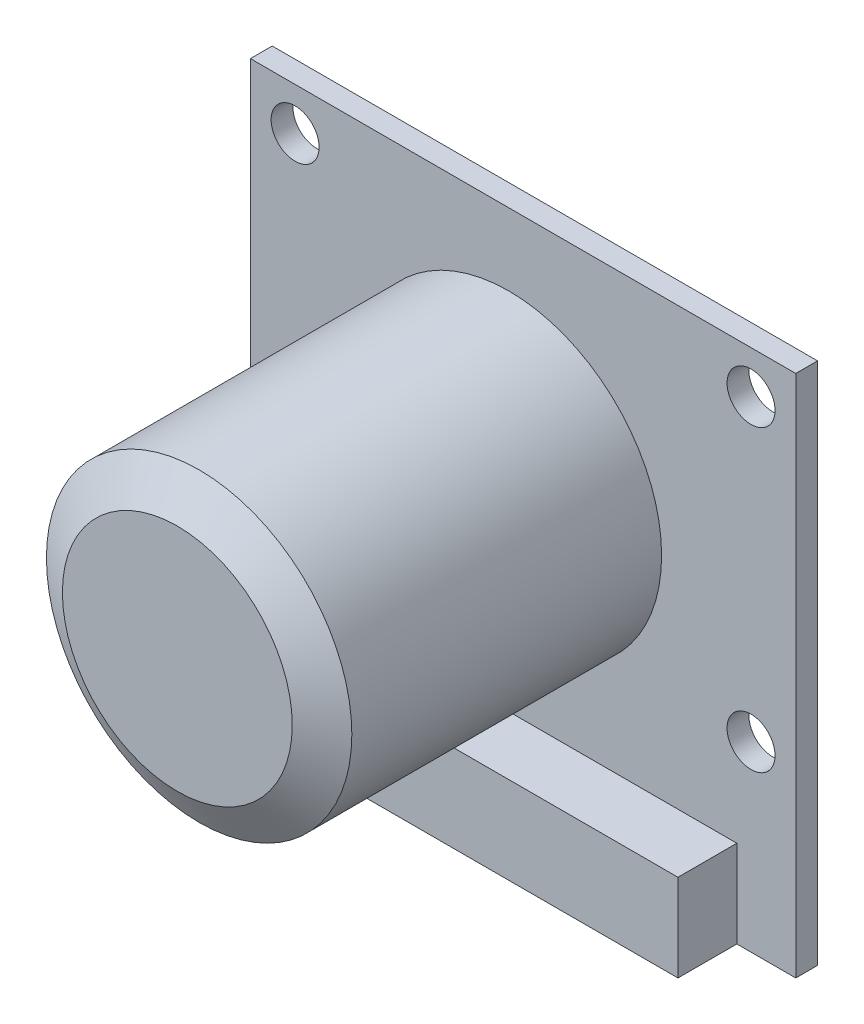
SolidWorks part; units mm, degrees
ref_plane "Plano frontal" through (0, 0, 0) normal (0, 0, 1) x (1, 0, 0)
ref_plane "Plano superior" through (0, 0, 0) normal (0, 1, 0) x (1, 0, 0)
ref_plane "Plano direito" through (0, 0, 0) normal (1, 0, 0) x (0, 0, -1)
sketch "Esboço1" plane through (0, 0, 0) normal (0, 0, 1) x (1, 0, 0)
  line L1 (-12.5, 12) -> (12.5, 12)
  line L2 (-12.5, 12) -> (-12.5, -12)
  line L3 (-12.5, -12) -> (12.5, -12)
  line L4 (12.5, 12) -> (12.5, -12)
  line L5 (-12.5, 12) -> (12.5, -12) construction
  line L6 (-12.5, -12) -> (12.5, 12) construction
  point P0 (0, 0)
  dimension "D1" = 25
  dimension "D2" = 24
extrude "Ressalto-extrusão1" add sketch "Esboço1" along normal blind 1
sketch "Esboço2" plane through (0, 0, 1) normal (0, 0, 1) x (1, 0, 0)
  line L0 (-12.5, -12) -> (12.5, -12) construction
  line L1 (-10.6, -8) -> (9.8, -8)
  line L2 (-10.6, -8) -> (-10.6, -12)
  line L3 (-10.6, -12) -> (9.8, -12)
  line L4 (9.8, -8) -> (9.8, -12)
  line L5 (12.5, -12) -> (12.5, 12) construction
  line L7 (-12.5, 12) -> (-12.5, -12) construction
  dimension "D1" = 4
  dimension "D2" = 20.4
  dimension "D3" = 2.7
  dimension "D4" = 1.9
extrude "Ressalto-extrusão2" add sketch "Esboço2" along normal blind 2.7
sketch "Esboço3" plane through (0, 0, 1) normal (0, 0, 1) x (1, 0, 0)
  line L0 (12.5, 12) -> (-12.5, 12) construction
  line L1 (12.5, -12) -> (12.5, 12) construction
  line L2 (-12.5, 12) -> (-12.5, -12) construction
  circle A0 centre (10.45, 10.05) radius 1.1
  circle A1 centre (-10.45, 10.05) radius 1.1
  circle A2 centre (10.45, -3.65) radius 1.1
  circle A3 centre (-10.45, -3.65) radius 1.1
  dimension "D4" = 1.95
  dimension "D5" = 2.2
  dimension "D6" = 2.2
  dimension "D7" = 2.2
  dimension "D8" = 13.7
  dimension "D9" = 2.2
  dimension "D10" = 13.7
  dimension "D1" = 1.95
  dimension "D2" = 2.05
  dimension "D3" = 2.05
extrude "Corte-extrusão1" cut sketch "Esboço3" against normal through all both and the other way through all
sketch "Esboço4" plane through (0, 0, 1) normal (0, 0, 1) x (1, 0, 0)
  line L0 (9.8, -8) -> (-10.6, -8) construction
  line L1 (12.5, -12) -> (12.5, 12) construction
  circle A0 centre (-0.65, 1.7) radius 7
  point P4 (-0.4, -8)
  dimension "D1" = 14
  dimension "D3" = 13.15
  dimension "D2" = 9.7
extrude "Ressalto-extrusão3" add sketch "Esboço4" along normal blind 15.2
chamfer "Chanfro1" distance 1 angle 60 1 edges at (6.35, 1.7, 16.2)
